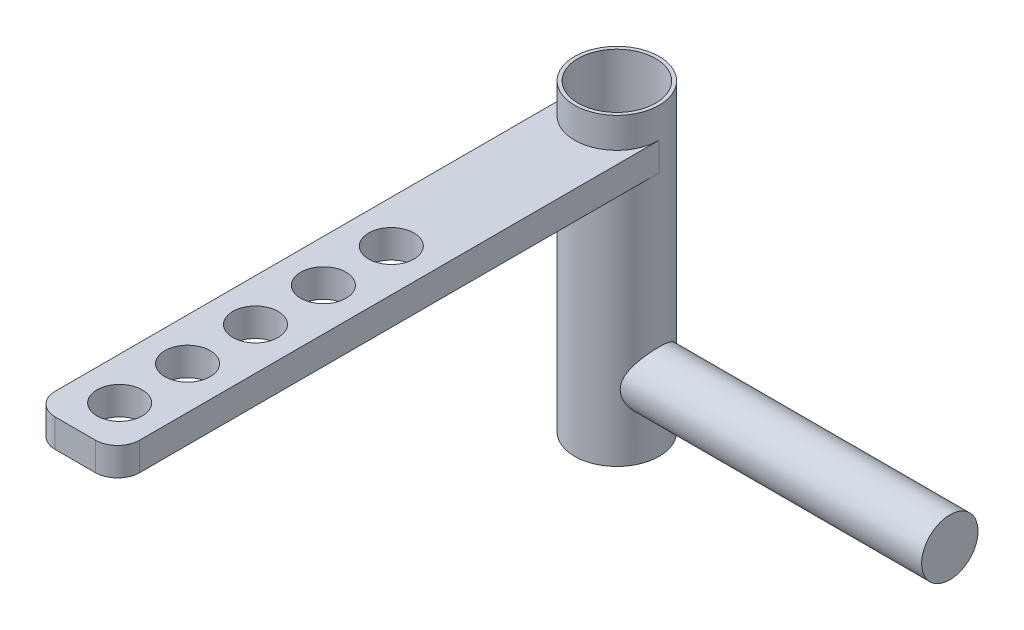
SolidWorks part; units mm, degrees
material "Alumina"
ref_plane "Front Plane" through (0, 0, 0) normal (0, 0, 1) x (1, 0, 0)
ref_plane "Top Plane" through (0, 0, 0) normal (0, 1, 0) x (1, 0, 0)
ref_plane "Right Plane" through (0, 0, 0) normal (1, 0, 0) x (0, 0, -1)
sketch "Sketch1" plane through (0, 0, 0) normal (0, 1, 0) x (1, 0, 0)
  circle A0 centre (0, 0) radius 9.525
  dimension "D1" = 19.05
extrude "Sleeve" add sketch "Sketch1" along normal blind 63.5 and the other way blind 5
sketch "Sketch2" plane through (0, 0, 0) normal (0, 0, 1) x (1, 0, 0)
  line L0 (0, -40.1638) -> (0, 40.1638) construction
  line L1 (9.525, 56.675) -> (-9.525, 56.675)
  line L2 (9.525, 56.675) -> (9.525, 50.325)
  line L3 (9.525, 50.325) -> (-9.525, 50.325)
  line L4 (-9.525, 56.675) -> (-9.525, 50.325)
  line L5 (9.525, 56.675) -> (-9.525, 50.325) construction
  line L6 (9.525, 50.325) -> (-9.525, 56.675) construction
  point P0 (0, 53.5)
  dimension "D2" = 19.05
  dimension "D3" = 53.5
extrude "Bracket" add sketch "Sketch2" along normal blind 122
sketch "Sketch4" plane through (0, 0, 0) normal (0, 1, 0) x (1, 0, 0)
  line L0 (0, -37.675) -> (0, 37.675) construction
  circle A0 centre (0, -50.8) radius 5.1
  circle A1 centre (0, -66.1) radius 5.1
  circle A2 centre (0, -81.4) radius 5.1
  circle A3 centre (0, -96.7) radius 5.1
  circle A4 centre (0, -112) radius 5.1
  dimension "D1" = 10.2
  dimension "D2" = 50.8
  dimension "D3" = 5
extrude "Bracket Hole" cut sketch "Sketch4" along normal through all
sketch "Sketch5" plane through (0, 0, 0) normal (1, 0, 0) x (0, 0, -1)
  line L0 (0, 37.675) -> (0, -37.675) construction
  circle A0 centre (0, 10) radius 6.35
  dimension "D2" = 12.7
  dimension "D1" = 10
extrude "Shaft" add sketch "Sketch5" along normal blind 75
sketch "Sketch6" plane through (0, 0, 0) normal (0, 1, 0) x (1, 0, 0)
  circle A0 centre (0, 0) radius 8.7313
  dimension "D1" = 17.4625
extrude "Sleeve Hole" cut sketch "Sketch6" along normal through all
fillet "Fillet1" radius 5 2 edges at (9.525, 53.5, 122) (-9.525, 53.5, 122)
equation "\"shaftDiameter\" = 25.4 / 4 * 2mm"
equation "\"shaftLength\"= 75mm"
equation "\"sleeveDiameter\"= 25.4 / 4 * 3mm"
equation "\"sleeveLength\"= 2.5 * 25.4mm"
equation "\"bracketLength\"= 122mm"
equation "\"D1@Sketch1\"=\"sleeveDiameter\""
equation "\"D1@Sleeve\" = \"sleeveLength\""
equation "\"D3@Sketch2\"=\"sleeveLength\"-10"
equation "\"D1@Bracket\" = \"bracketLength\""
equation "\"tieBarHoleDiameter\"= 10.2mm"
equation "\"D1@Sketch4\"=\"tieBarHoleDiameter\""
equation "\"D2@Sketch4\"=50.8"
equation "\"D2@Sketch5\"=\"shaftDiameter\""
equation "\"D1@Shaft\" = \"shaftLength\""
equation "\"sleeveWallThickness\"= 25.4 / 16"
equation "\"D1@Sketch6\"=\"sleeveDiameter\"-\"sleeveWallThickness\""
